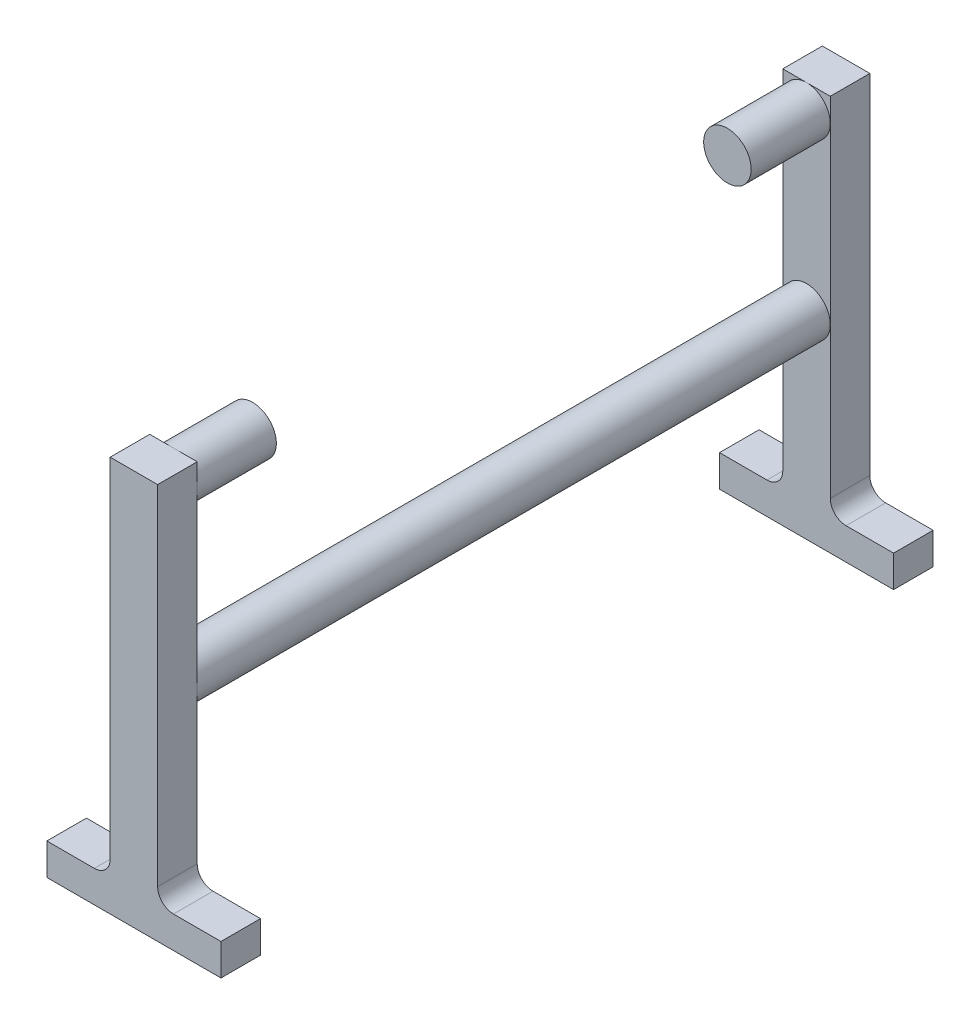
SolidWorks part; units mm, degrees
ref_plane "Front Plane" through (0, 0, 0) normal (0, 0, 1) x (1, 0, 0)
ref_plane "Top Plane" through (0, 0, 0) normal (0, 1, 0) x (1, 0, 0)
ref_plane "Right Plane" through (0, 0, 0) normal (1, 0, 0) x (0, 0, -1)
sketch "Sketch1" plane through (0, 0, 0) normal (0, 0, 1) x (1, 0, 0)
  circle A0 centre (0, 0) radius 3
  dimension "D1" = 6
extrude "Boss-Extrude1" add sketch "Sketch1" along normal mid plane 80
sketch "Sketch2" plane through (0, 0, 40) normal (0, 0, 1) x (1, 0, 0)
  line L8 (3, -25) -> (-3, -25)
  line L9 (3, -25) -> (3, 25)
  line L10 (3, 25) -> (-3, 25)
  line L11 (-3, -25) -> (-3, 25)
  line L12 (3, -25) -> (-3, 25) construction
  line L13 (3, 25) -> (-3, -25) construction
  circle A1 centre (0, 0) radius 3 construction
  point P0 (0, 0)
  dimension "D1" = 50
extrude "Boss-Extrude2" add sketch "Sketch2" along normal blind 5
sketch "Sketch9" plane through (0, -25, 0) normal (0, -1, 0) x (1, 0, 0)
  line L0 (-3, 45) -> (3, 45) construction
  line L1 (11, 40) -> (-11, 40)
  line L2 (11, 40) -> (11, 45)
  line L3 (11, 45) -> (-11, 45)
  line L4 (-11, 40) -> (-11, 45)
  line L5 (11, 40) -> (-11, 45) construction
  line L6 (11, 45) -> (-11, 40) construction
  line L7 (-3, 40) -> (3, 40) construction
  line L8 (3, 45) -> (3, 40) construction
  line L9 (-3, 45) -> (-3, 40) construction
  point P0 (0, 42.5)
  dimension "D1" = 8
  dimension "D2" = 8
extrude "Boss-Extrude5" add sketch "Sketch9" against normal blind 4
fillet "Fillet1" radius 2 2 edges at (-3, -21, 42.5) (3, -21, 42.5)
sketch "Sketch11" plane through (0, 0, 40) normal (0, 0, -1) x (-1, 0, 0)
  line L1 (-3, 25) -> (3, 25) construction
  line L3 (3, 25) -> (3, 0) construction
  line L4 (-3, 0) -> (-3, 25) construction
  circle A0 centre (0, 22) radius 3
extrude "Boss-Extrude7" add sketch "Sketch11" along normal blind 10
mirror "Mirror5" about plane through (0, 0, 0) normal (0, 0, 1) of "Boss-Extrude7", "Boss-Extrude2", "Boss-Extrude5", "Fillet1"
mirror "Mirror1" about plane through (0, 0, 0) normal (0, 0, 1) of "Boss-Extrude2"
